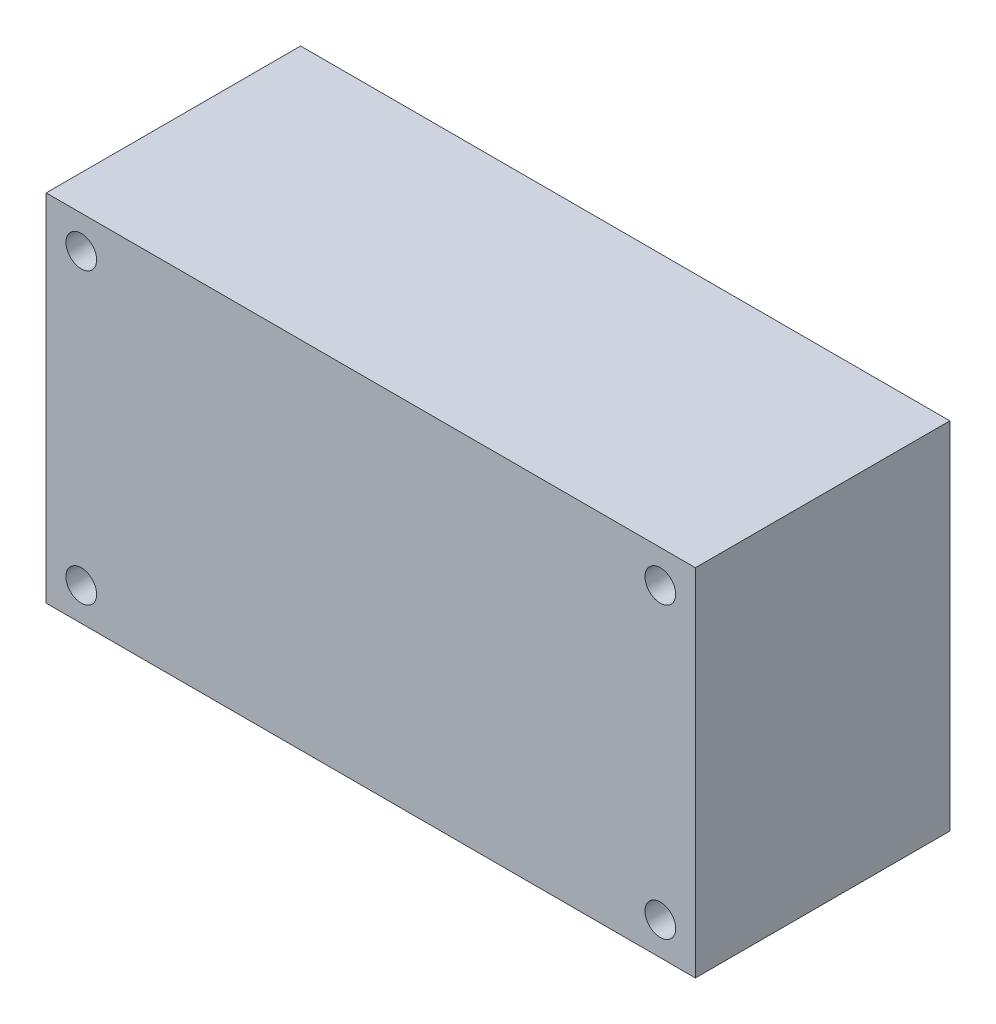
SolidWorks part; units mm, degrees
ref_plane "前基準面" through (0, 0, 0) normal (0, 0, 1) x (1, 0, 0)
ref_plane "上基準面" through (0, 0, 0) normal (0, 1, 0) x (1, 0, 0)
ref_plane "右基準面" through (0, 0, 0) normal (1, 0, 0) x (0, 0, -1)
sketch "草圖1" plane through (0, 0, 0) normal (0, 0, 1) x (1, 0, 0)
  line L1 (-37, 20.25) -> (37, 20.25)
  line L2 (-37, 20.25) -> (-37, -20.25)
  line L3 (-37, -20.25) -> (37, -20.25)
  line L4 (37, 20.25) -> (37, -20.25)
  line L5 (-37, 20.25) -> (37, -20.25) construction
  line L6 (-37, -20.25) -> (37, 20.25) construction
  line L7 (-33, 16.5) -> (33, 16.5) construction
  line L8 (-33, 16.5) -> (-33, -16.5) construction
  line L9 (-33, -16.5) -> (33, -16.5) construction
  line L10 (33, 16.5) -> (33, -16.5) construction
  line L11 (-33, 16.5) -> (33, -16.5) construction
  line L12 (-33, -16.5) -> (33, 16.5) construction
  circle A0 centre (-33, 16.5) radius 1.75
  circle A1 centre (-33, -16.5) radius 1.75
  circle A2 centre (33, -16.5) radius 1.75
  circle A3 centre (33, 16.5) radius 1.75
  point P0 (0, 0)
  point P6 (0, 0)
  dimension "D5" = 3.5
  dimension "D1" = 74
  dimension "D2" = 40.5
  dimension "D3" = 33
  dimension "D4" = 66
extrude "伸長1" add sketch "草圖1" along normal blind 29
